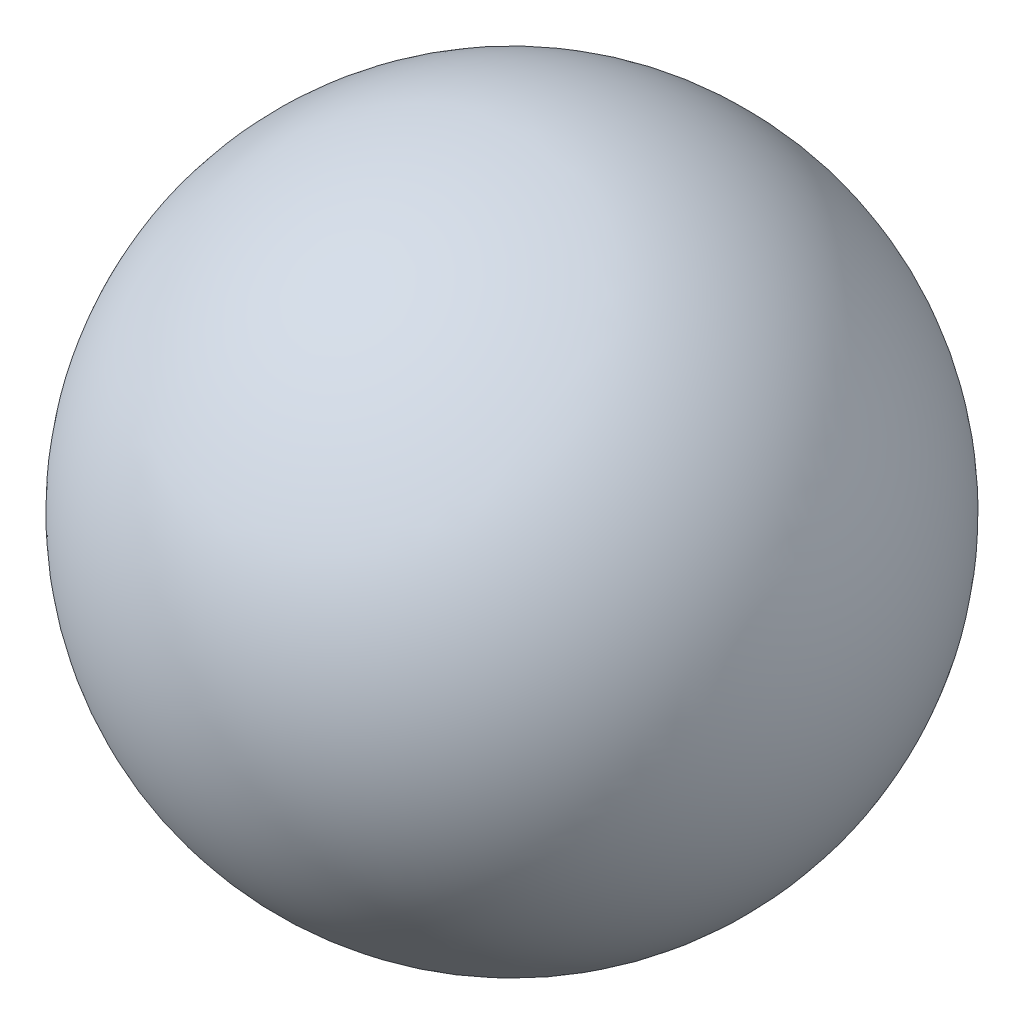
SolidWorks part; units mm, degrees
ref_plane "Face" through (0, 0, 0) normal (0, 0, 1) x (1, 0, 0)
ref_plane "Dessus" through (0, 0, 0) normal (0, 1, 0) x (1, 0, 0)
ref_plane "Droite" through (0, 0, 0) normal (1, 0, 0) x (0, 0, -1)
sketch "Esquisse1" plane through (0, 0, 0) normal (0, 0, 1) x (1, 0, 0)
  line L0 (-3.5, 0) -> (3.5, 0)
  line L1 (-4.415, 0) -> (4.415, 0) construction
  arc A0 (3.5, 0) -> (-3.5, 0) centre (0, 0) ccw
  dimension "D1" = 7
revolve "Base-Révolution" add sketch "Esquisse1" angle 360 about L1
